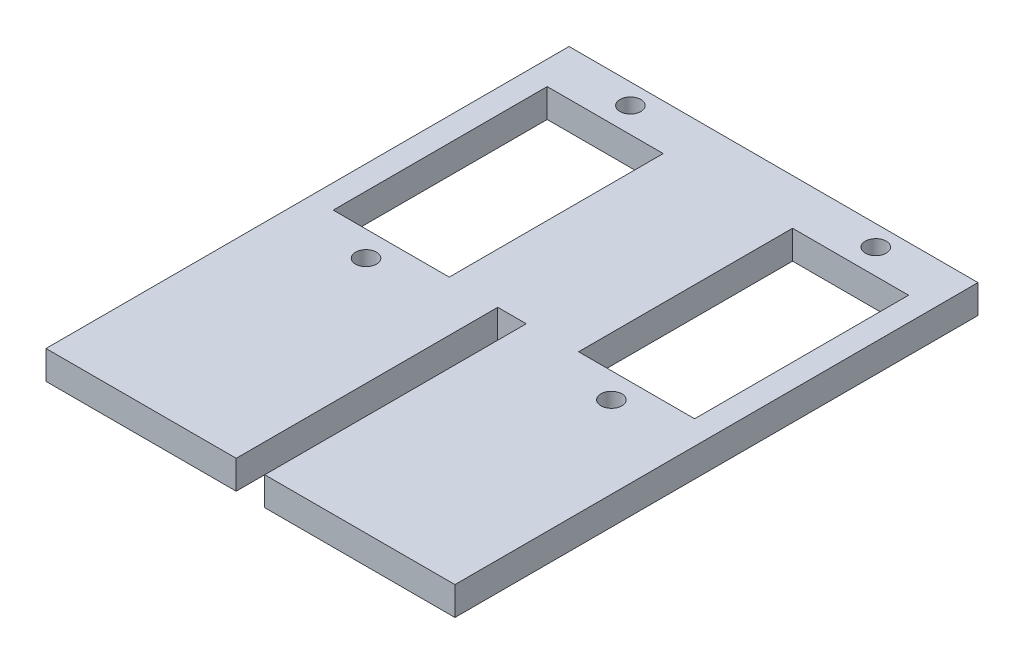
SolidWorks part; units mm, degrees
ref_plane "Front Plane" through (0, 0, 0) normal (0, 0, 1) x (1, 0, 0)
ref_plane "Top Plane" through (0, 0, 0) normal (0, 1, 0) x (1, 0, 0)
ref_plane "Right Plane" through (0, 0, 0) normal (1, 0, 0) x (0, 0, -1)
sketch "Sketch1" plane through (0, 0, 0) normal (0, 1, 0) x (1, 0, 0)
  line L1 (-21.5, -27.5) -> (21.5, -27.5)
  line L2 (-21.5, -27.5) -> (-21.5, 27.5)
  line L3 (-21.5, 27.5) -> (21.5, 27.5)
  line L4 (21.5, -27.5) -> (21.5, 27.5)
  line L5 (0, 27.5) -> (0, -27.5) construction
  line L6 (-21.5, 0) -> (21.5, 0) construction
  point P0 (0, 0)
  dimension "D1" = 43
  dimension "D2" = 55
extrude "Boss-Extrude1" add sketch "Sketch1" along normal blind 3
sketch "Sketch2" plane through (0, 3, 0) normal (0, 1, 0) x (1, 0, 0)
  line L0 (-21.5, -27.5) -> (21.5, -27.5) construction
  line L1 (-1.5, -27.5) -> (1.5, -27.5)
  line L2 (-1.5, -27.5) -> (-1.5, 0)
  line L3 (-1.5, 0) -> (1.5, 0)
  line L4 (1.5, -27.5) -> (1.5, 0)
  line L5 (-21.5, 27.5) -> (-21.5, -27.5) construction
  line L6 (21.5, -27.5) -> (21.5, 27.5) construction
  line L7 (0, 0) -> (21.5, 0) construction
  dimension "D1" = 20
  dimension "D2" = 20
extrude "Cut-Extrude1" cut sketch "Sketch2" against normal blind 10
sketch "Sketch3" plane through (0, 0, 0) normal (0, -1, 0) x (1, 0, 0)
  line L0 (18.15, -0.2) -> (21.5, -0.2) construction
  line L1 (18.15, -22.7) -> (21.5, -22.7) construction
  line L2 (21.5, 27.5) -> (21.5, -27.5) construction
  line L3 (7.65, -0.2) -> (18.15, -0.2) construction
  line L4 (19, -21.85) -> (19, -22.7) construction
  line L5 (7.65, -0.2) -> (6.5416, -0.2) construction
  line L6 (6.8, -1.05) -> (6.8, -0.2) construction
  line L7 (0, 0) -> (0, -27.5) construction
  line L8 (6.8, -0.2) -> (19, -0.2)
  line L9 (6.8, -0.2) -> (6.8, -22.7)
  line L10 (6.8, -22.7) -> (19, -22.7)
  line L11 (19, -0.2) -> (19, -22.7)
  line L12 (21.5, -27.5) -> (-21.5, -27.5) construction
  line L13 (-6.8, -22.7) -> (-19, -22.7)
  line L14 (-19, -0.2) -> (-19, -22.7)
  line L15 (-6.8, -0.2) -> (-6.8, -22.7)
  line L16 (-6.8, -0.2) -> (-19, -0.2)
  arc A0 (19, -1.05) -> (18.15, -0.2) centre (18.15, -1.05) ccw construction
  circle A1 centre (12.9, -25.35) radius 1.1
  circle A2 centre (12.9, 2.45) radius 1.1
  circle A3 centre (-12.9, -25.35) radius 1.1
  circle A4 centre (-12.9, 2.45) radius 1.1
extrude "Cut-Extrude2" cut sketch "Sketch3" against normal blind 10
